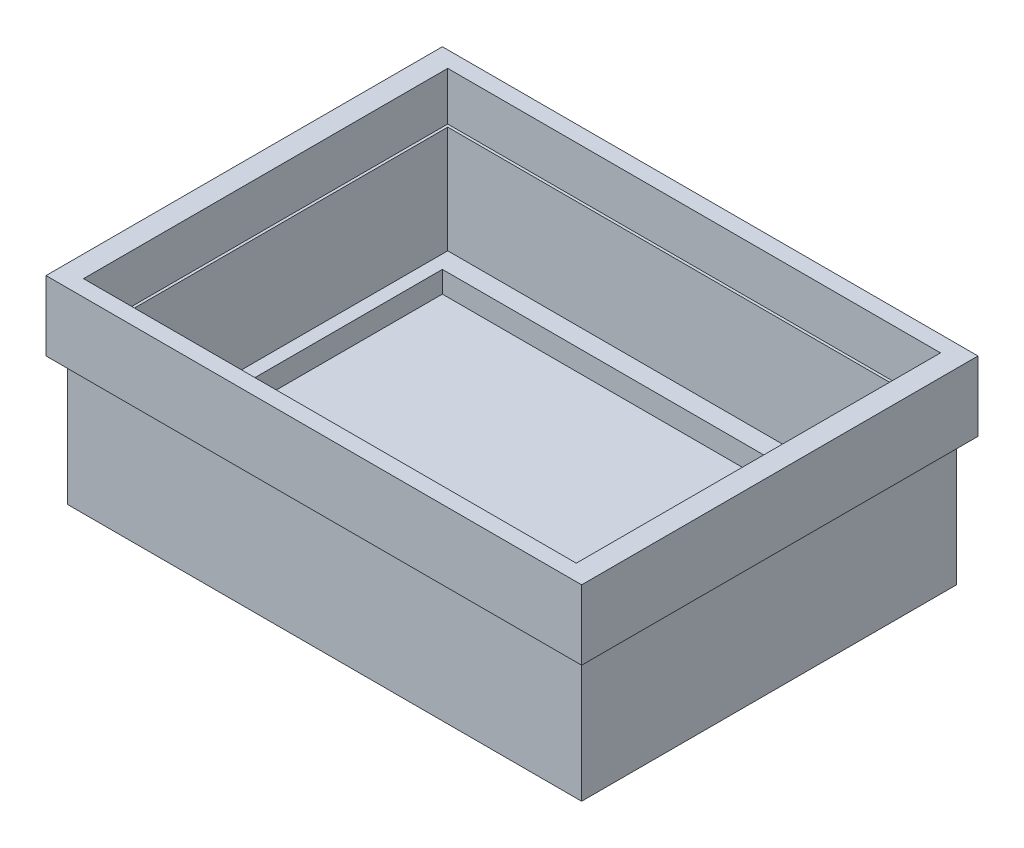
SolidWorks part; units mm, degrees
ref_plane "Front Plane" through (0, 0, 0) normal (0, 0, 1) x (1, 0, 0)
ref_plane "Top Plane" through (0, 0, 0) normal (0, 1, 0) x (1, 0, 0)
ref_plane "Right Plane" through (0, 0, 0) normal (1, 0, 0) x (0, 0, -1)
sketch "Sketch2" plane through (0, 0, 0) normal (0, 1, 0) x (1, 0, 0)
  line L1 (-215, 150) -> (215, 150)
  line L2 (-215, 150) -> (-215, -150)
  line L3 (-215, -150) -> (215, -150)
  line L4 (215, 150) -> (215, -150)
  line L5 (-215, 150) -> (215, -150) construction
  line L6 (-215, -150) -> (215, 150) construction
  line L7 (-237.5, 175) -> (237.5, 175) construction
  line L8 (-237.5, 175) -> (-237.5, -175) construction
  line L9 (-237.5, -175) -> (237.5, -175) construction
  line L10 (237.5, 175) -> (237.5, -175) construction
  line L11 (-237.5, 175) -> (237.5, -175) construction
  line L12 (-237.5, -175) -> (237.5, 175) construction
  line L13 (-250, 185) -> (250, 185)
  line L14 (-250, 185) -> (-250, -185)
  line L15 (-250, -185) -> (250, -185)
  line L16 (250, 185) -> (250, -185)
  line L17 (-250, 185) -> (250, -185) construction
  line L18 (-250, -185) -> (250, 185) construction
  point P0 (0, 0)
  point P6 (0, 0)
  point P11 (0, 0)
  dimension "D1" = 300
  dimension "D2" = 430
  dimension "D3" = 475
  dimension "D4" = 350
  dimension "D5" = 500
  dimension "D6" = 370
extrude "Boss-Extrude1" add sketch "Sketch2" along normal blind 120
sketch "Sketch4" plane through (0, 120, 0) normal (0, 1, 0) x (1, 0, 0)
  line L1 (-230, 170) -> (230, 170)
  line L2 (-230, 170) -> (-230, -170)
  line L3 (-230, -170) -> (230, -170)
  line L4 (230, 170) -> (230, -170)
  line L5 (-230, 170) -> (230, -170) construction
  line L6 (-230, -170) -> (230, 170) construction
  line L7 (-250, 185) -> (250, 185)
  line L8 (-250, 185) -> (-250, -185)
  line L9 (-250, -185) -> (250, -185)
  line L10 (250, 185) -> (250, -185)
  line L11 (-250, 185) -> (250, -185) construction
  line L12 (-250, -185) -> (250, 185) construction
  point P0 (0, 0)
  point P6 (0, 0)
  dimension "D1" = 460
  dimension "D2" = 340
extrude "Boss-Extrude2" add sketch "Sketch4" along normal blind 45
sketch "Sketch5" plane through (0, 0, 0) normal (0, -1, 0) x (1, 0, 0)
  line L1 (-250, -185) -> (250, -185)
  line L2 (-250, -185) -> (-250, 185)
  line L3 (-250, 185) -> (250, 185)
  line L4 (250, -185) -> (250, 185)
  line L5 (-250, -185) -> (250, 185) construction
  line L6 (-250, 185) -> (250, -185) construction
  point P0 (0, 0)
extrude "Boss-Extrude3" add sketch "Sketch5" along normal blind 20
sketch "Sketch6" plane through (0, -20, 0) normal (0, -1, 0) x (1, 0, 0)
  line L1 (-250, -185) -> (250, -185)
  line L2 (-250, -185) -> (-250, 185)
  line L3 (-250, 185) -> (250, 185)
  line L4 (250, -185) -> (250, 185)
  line L5 (-250, -185) -> (250, 185) construction
  line L6 (-250, 185) -> (250, -185) construction
  line L7 (-240, -175) -> (240, -175)
  line L8 (-240, -175) -> (-240, 175)
  line L9 (-240, 175) -> (240, 175)
  line L10 (240, -175) -> (240, 175)
  line L11 (-240, -175) -> (240, 175) construction
  line L12 (-240, 175) -> (240, -175) construction
  point P0 (0, 0)
  point P7 (0, 0)
  dimension "D1" = 10
  dimension "D2" = 10
extrude "Cut-Extrude1" cut sketch "Sketch6" against normal blind 120
sketch "Sketch8" plane through (0, 120, 0) normal (0, 1, 0) x (1, 0, 0)
  line L1 (-227.5, -167.5) -> (227.5, -167.5)
  line L2 (-227.5, -167.5) -> (-227.5, 167.5)
  line L3 (-227.5, 167.5) -> (227.5, 167.5)
  line L4 (227.5, -167.5) -> (227.5, 167.5)
  line L5 (-227.5, -167.5) -> (227.5, 167.5) construction
  line L6 (-227.5, 167.5) -> (227.5, -167.5) construction
  point P0 (0, 0)
  dimension "D1" = 335
  dimension "D2" = 455
extrude "Cut-Extrude2" cut sketch "Sketch8" against normal blind 100
